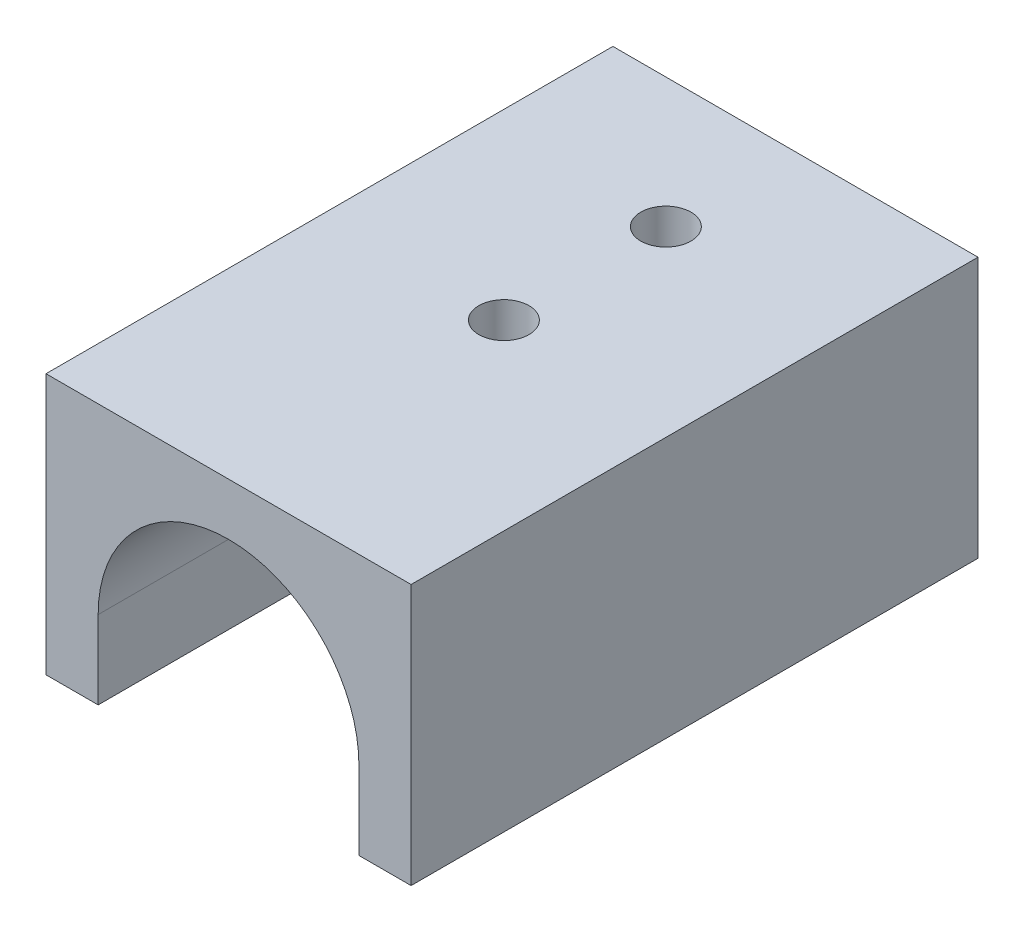
SolidWorks part; units mm, degrees
ref_plane "Front Plane" through (0, 0, 0) normal (0, 0, 1) x (1, 0, 0)
ref_plane "Top Plane" through (0, 0, 0) normal (0, 1, 0) x (1, 0, 0)
ref_plane "Right Plane" through (0, 0, 0) normal (1, 0, 0) x (0, 0, -1)
sketch "Sketch1" plane through (0, 0, 0) normal (0, 0, 1) x (1, 0, 0)
  line L0 (-11.27, 11.27) -> (11.27, 11.27)
  line L1 (-11.27, 11.27) -> (-11.27, -4.83)
  line L2 (11.27, 11.27) -> (11.27, -4.83)
  line L3 (8.05, -4.83) -> (8.05, 0)
  line L4 (11.27, -4.83) -> (8.05, -4.83)
  line L5 (-11.27, -4.83) -> (-8.05, -4.83)
  line L6 (-8.05, -4.83) -> (-8.05, 0)
  arc A0 (-8.05, 0) -> (8.05, 0) centre (0, 0) cw
  dimension "D1" = 8.05
  dimension "D3" = 11.27
  dimension "D4" = 16.1
  dimension "D2" = 22.54
extrude "Boss-Extrude1" add sketch "Sketch1" along normal mid plane 35
sketch "Sketch2" plane through (0, 11.27, 0) normal (0, 1, 0) x (1, 0, 0)
  line L0 (0, -44.7868) -> (0, 44.7868) construction
  line L1 (11.27, 17.5) -> (-11.27, 17.5) construction
  circle A0 centre (0, 9.5) radius 1.55
  circle A1 centre (0, -0.5) radius 1.55
  dimension "D3" = 3.1
  dimension "D1" = 10
  dimension "D2" = 8
extrude "Cut-Extrude1" cut sketch "Sketch2" against normal up to surface (3.22 mm away)
equation "\"tubeRad\" = 8.05"
equation "\"D1@Sketch1\"=\"tubeRad\""
equation "\"D3@Sketch1\"=\"tubeRad\"+(\"tubeRad\"*2/5)"
equation "\"D4@Sketch1\"=\"tubeRad\"*2"
equation "\"MountHoleSize\"= 3.1"
equation "\"D3@Sketch2\"=\"MountHoleSize\""
equation "\"D2@Sketch1\"=\"tubeRad\"*2 +2*(\"tubeRad\"*2/5)"
